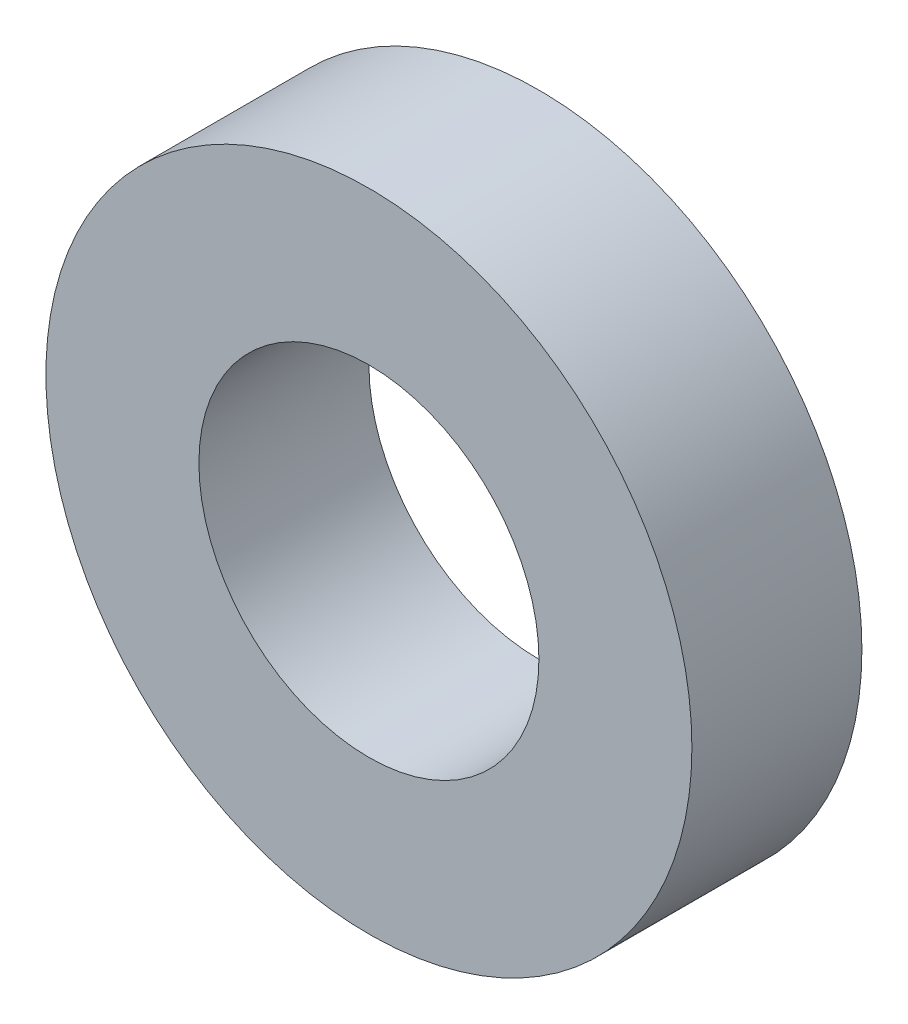
SolidWorks part; units mm, degrees
ref_plane "前视基准面" through (0, 0, 0) normal (0, 0, 1) x (1, 0, 0)
ref_plane "上视基准面" through (0, 0, 0) normal (0, 1, 0) x (1, 0, 0)
ref_plane "右视基准面" through (0, 0, 0) normal (1, 0, 0) x (0, 0, -1)
sketch "草图1" plane through (0, 0, 0) normal (0, 0, 1) x (1, 0, 0)
  circle A0 centre (0, 0) radius 9.5
  circle A1 centre (0, 0) radius 5
  dimension "D1" = 19
  dimension "D2" = 10
extrude "拉伸1" add sketch "草图1" along normal blind 5
